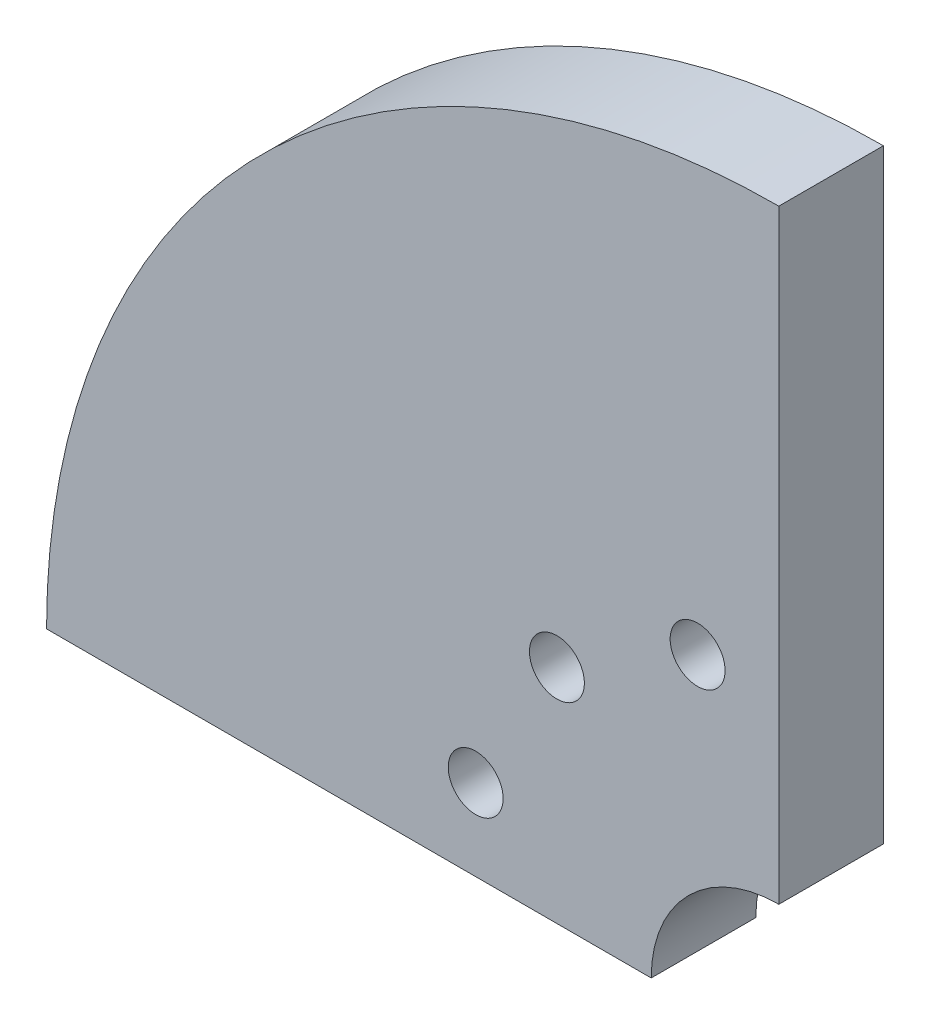
SolidWorks part; units mm, degrees
ref_plane "Front Plane" through (0, 0, 0) normal (0, 0, 1) x (1, 0, 0)
ref_plane "Top Plane" through (0, 0, 0) normal (0, 1, 0) x (1, 0, 0)
ref_plane "Right Plane" through (0, 0, 0) normal (1, 0, 0) x (0, 0, -1)
sketch "Sketch1" plane through (0, 0, 0) normal (0, 0, 1) x (1, 0, 0)
  line L0 (0, 70) -> (0, 0)
  line L1 (0, 0) -> (-70, 0)
  arc A0 (0, 70) -> (-70, 0) centre (0, 0) ccw
  dimension "D1" = 70
extrude "Boss-Extrude1" add sketch "Sketch1" along normal blind 10
sketch "Sketch2" plane through (0, 0, 0) normal (0, 0, 1) x (1, 0, 0)
  line L0 (0, 0) -> (-7.7646, 28.9778) construction
  line L1 (0, 0) -> (-21.2132, 21.2132) construction
  line L2 (0, 0) -> (-34.9836, 9.1821) construction
  circle A3 centre (-7.7646, 28.9778) radius 2.625
  circle A4 centre (-21.2132, 21.2132) radius 2.625
  circle A5 centre (-28.9778, 7.7646) radius 2.625
  point P14 (0, 0)
  dimension "D1" = 5.25
  dimension "D2" = 3
extrude "Cut-Extrude1" cut sketch "Sketch2" along normal through all
sketch "Sketch3" plane through (0, 0, 0) normal (0, 0, 1) x (1, 0, 0)
  circle A0 centre (0, 0) radius 12.2
  dimension "D1" = 24.4
extrude "Cut-Extrude2" cut sketch "Sketch3" along normal blind 20
sketch "Sketch4" plane through (0, 0, 0) normal (0, 0, 1) x (1, 0, 0)
  line L0 (0, 0) -> (-12.2939, 45.8815) construction
  line L1 (-20.1394, 31.4646) -> (-35.6958, 47.0209)
  line L6 (-1.709, 37.3189) -> (-17.1638, 33.1778)
  line L7 (-1.709, 37.3189) -> (-7.403, 58.5692)
  line L8 (-7.403, 58.5692) -> (-22.8578, 54.4281)
  line L9 (-17.1638, 33.1778) -> (-22.8578, 54.4281)
  line L10 (-1.709, 37.3189) -> (-22.8578, 54.4281) construction
  line L11 (-7.403, 58.5692) -> (-17.1638, 33.1778) construction
  line L12 (-20.1394, 31.4646) -> (-31.4531, 20.1509)
  line L13 (-31.4531, 20.1509) -> (-47.0095, 35.7072)
  line L14 (-35.6958, 47.0209) -> (-47.0095, 35.7072)
  line L15 (-33.1736, 17.1794) -> (-54.4239, 22.8734)
  line L16 (-33.1736, 17.1794) -> (-37.3147, 1.7246)
  line L17 (-37.3147, 1.7246) -> (-58.565, 7.4186)
  line L18 (-54.4239, 22.8734) -> (-58.565, 7.4186)
  circle A0 centre (0, 0) radius 35 construction
  circle A1 centre (0, 0) radius 60 construction
  point P6 (-12.2939, 45.8815)
  point P22 (0, 0)
  dimension "D1" = 70
  dimension "D2" = 120
  dimension "D3" = 22
  dimension "D4" = 16
  dimension "D5" = 3
extrude "Cut-Extrude3" cut sketch "Sketch4" along normal blind 4 contours L1 L14 L13 L12 | L9 L8 L7 L6 | L15 L18 L17 L16
